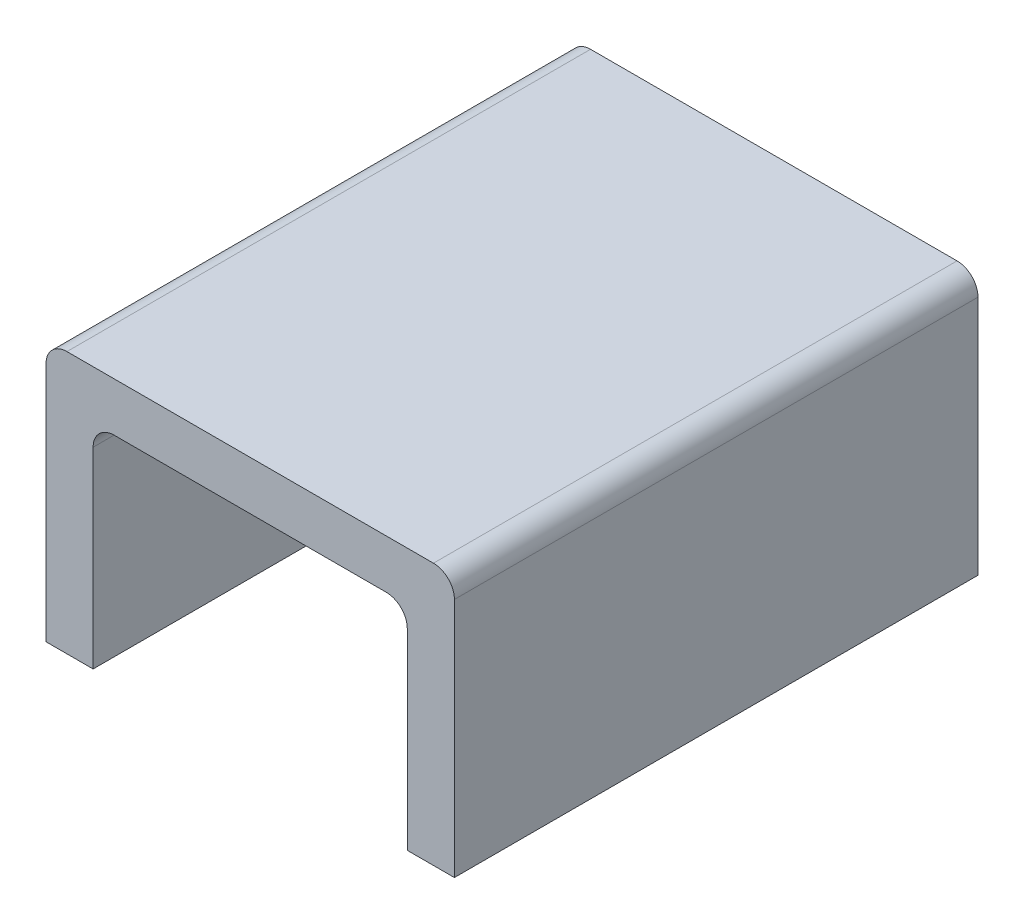
SolidWorks part; units mm, degrees
ref_plane "Plan de face" through (0, 0, 0) normal (0, 0, 1) x (1, 0, 0)
ref_plane "Plan de dessus" through (0, 0, 0) normal (0, 1, 0) x (1, 0, 0)
ref_plane "Plan de droite" through (0, 0, 0) normal (1, 0, 0) x (0, 0, -1)
sketch "Esquisse2" plane through (0, 0, 0) normal (0, 0, 1) x (1, 0, 0)
  line L0 (-32.625, -8.9205) -> (-32.625, 9.0795)
  line L1 (-30.625, 11.0795) -> (4.375, 11.0795)
  line L2 (6.375, 9.0795) -> (6.375, -13.9205)
  line L3 (6.375, -13.9205) -> (1.875, -13.9205)
  line L4 (1.875, -13.9205) -> (1.875, 4.4205)
  line L5 (-0.125, 6.4205) -> (-26.125, 6.4205)
  line L6 (-28.125, 4.4205) -> (-28.125, -13.9205)
  line L7 (-28.125, -13.9205) -> (-32.625, -13.9205)
  line L8 (-32.625, -13.9205) -> (-32.625, -8.9205)
  line L9 (-28.125, -13.9205) -> (1.875, -13.9205) construction
  line L10 (-28.125, 6.4205) -> (-32.625, 6.4205) construction
  line L11 (1.875, 6.4205) -> (6.375, 6.4205) construction
  arc A0 (1.875, 4.4205) -> (-0.125, 6.4205) centre (-0.125, 4.4205) ccw
  arc A1 (4.375, 11.0795) -> (6.375, 9.0795) centre (4.375, 9.0795) cw
  arc A2 (-32.625, 9.0795) -> (-30.625, 11.0795) centre (-30.625, 9.0795) cw
  arc A3 (-26.125, 6.4205) -> (-28.125, 4.4205) centre (-26.125, 4.4205) ccw
  point P18 (-32.625, 11.0795)
  dimension "D3" = 2
  dimension "D1" = 25
  dimension "D2" = 30
  dimension "D4" = 35
extrude "Boss.-Extru.1" add sketch "Esquisse2" along normal blind 50
